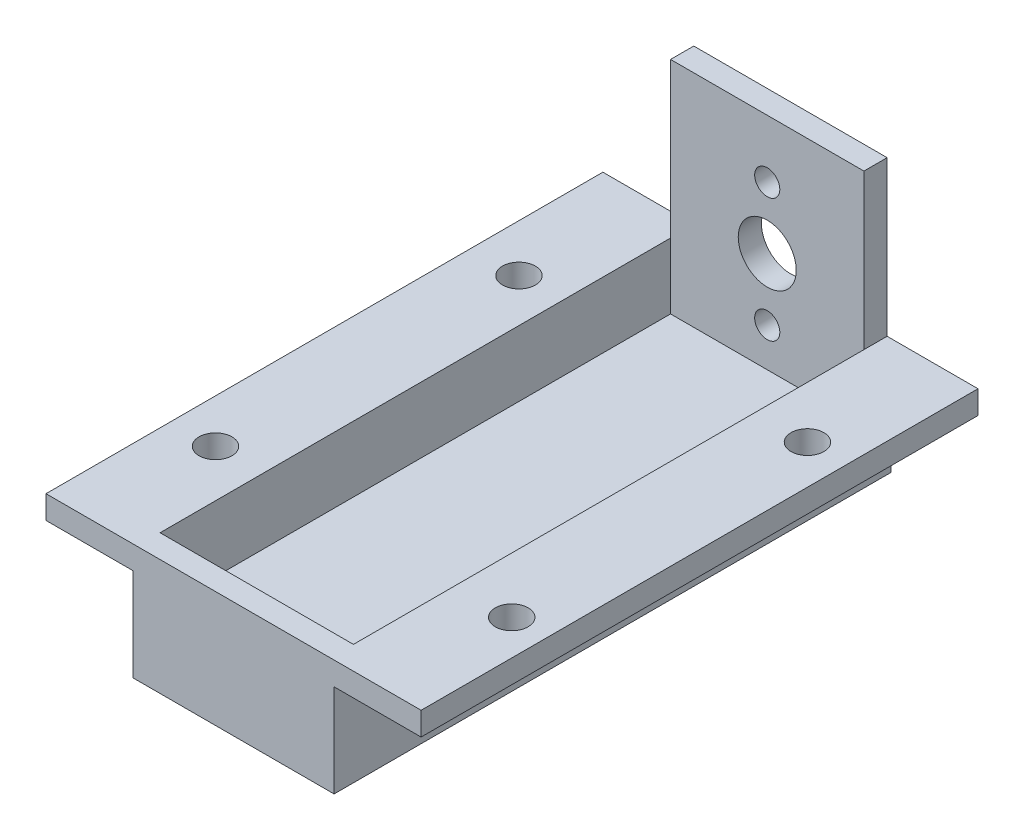
SolidWorks part; units mm, degrees
ref_plane "Alzado" through (0, 0, 0) normal (0, 0, 1) x (1, 0, 0)
ref_plane "Planta" through (0, 0, 0) normal (0, 1, 0) x (1, 0, 0)
ref_plane "Vista lateral" through (0, 0, 0) normal (1, 0, 0) x (0, 0, -1)
sketch "Croquis1" plane through (0, 0, 0) normal (0, 0, 1) x (1, 0, 0)
  line L0 (12.5, 0) -> (-12.5, 0)
  line L1 (-12.5, 0) -> (-12.5, -20)
  line L2 (0, 0) -> (0, -35) construction
  line L3 (-12.5, -20) -> (-24.25, -20)
  line L4 (-24.25, -20) -> (-24.25, -23)
  line L5 (-24.25, -23) -> (-13, -23)
  line L6 (-13, -23) -> (-13, -35)
  line L7 (-13, -35) -> (13, -35)
  line L8 (13, -23) -> (13, -35)
  line L9 (24.25, -23) -> (13, -23)
  line L10 (24.25, -20) -> (24.25, -23)
  line L11 (12.5, -20) -> (24.25, -20)
  line L12 (12.5, 0) -> (12.5, -20)
  dimension "D1" = 12.5
  dimension "D2" = 20
  dimension "D3" = 11.75
  dimension "D4" = 3
  dimension "D5" = 11.25
  dimension "D6" = 12
extrude "Saliente-Extruir1" add sketch "Croquis1" along normal blind 72 contours L7 L8 L9 L10 L11 L12 L0 L1 L3 L4 L5 L6
sketch "Croquis4" plane through (0, 0, 72) normal (0, 0, 1) x (1, 0, 0)
  line L0 (12.5, 0) -> (12.5, -20) construction
  line L1 (-12.5, 0) -> (12.5, 0)
  line L2 (-12.5, 0) -> (-12.5, -20)
  line L3 (-12.5, -20) -> (12.5, -20)
  line L4 (12.5, 0) -> (12.5, -20)
extrude "Cortar-Extruir1" cut sketch "Croquis4" against normal blind 69
sketch "Croquis5" plane through (0, -20, 0) normal (0, 1, 0) x (1, 0, 0)
  line L0 (-12.5, -3) -> (12.5, -3)
  line L1 (12.5, -3) -> (12.5, -69)
  line L2 (12.5, -69) -> (-12.5, -69)
  line L3 (-12.5, -69) -> (-12.5, -3)
  dimension "D1" = 66
extrude "Cortar-Extruir2" cut sketch "Croquis5" against normal blind 8.5
sketch "Croquis7" plane through (0, -20, 0) normal (0, 1, 0) x (1, 0, 0)
  line L0 (-18.1, -17) -> (-24.25, -17) construction
  line L1 (-18.6, -55.7379) -> (-24.25, -55.7379) construction
  line L2 (-24.25, -72) -> (-24.25, 0) construction
  line L3 (-18.1, -17) -> (19.2, -17) construction
  line L4 (-18.6, -55.7379) -> (19.7, -55.7379) construction
  circle A0 centre (-18.1, -17) radius 2.125
  circle A1 centre (-18.6, -55.7379) radius 2.125
  circle A2 centre (19.2, -17) radius 2.125
  circle A3 centre (19.7, -55.7379) radius 2.125
  dimension "D3" = 4.25
  dimension "D7" = 4.25
  dimension "D8" = 4.25
  dimension "D9" = 4.25
  dimension "D1" = 6.15
  dimension "D2" = 37.3
  dimension "D4" = 5.65
  dimension "D5" = 38.3
extrude "Cortar-Extruir3" cut sketch "Croquis7" against normal blind 8.5
sketch "Croquis8" plane through (0, 0, 0) normal (0, 0, -1) x (-1, 0, 0)
  line L2 (-12.5, 0) -> (12.5, 0) construction
  circle A0 centre (0, -15.5) radius 3.75
  circle A1 centre (0, -23.5) radius 1.625
  circle A2 centre (0, -7.5) radius 1.625
  dimension "D2" = 7.5
  dimension "D4" = 3.25
  dimension "D5" = 3.25
  dimension "D1" = 8
  dimension "D3" = 8
  dimension "D6" = 15.5
extrude "Cortar-Extruir4" cut sketch "Croquis8" against normal blind 3
